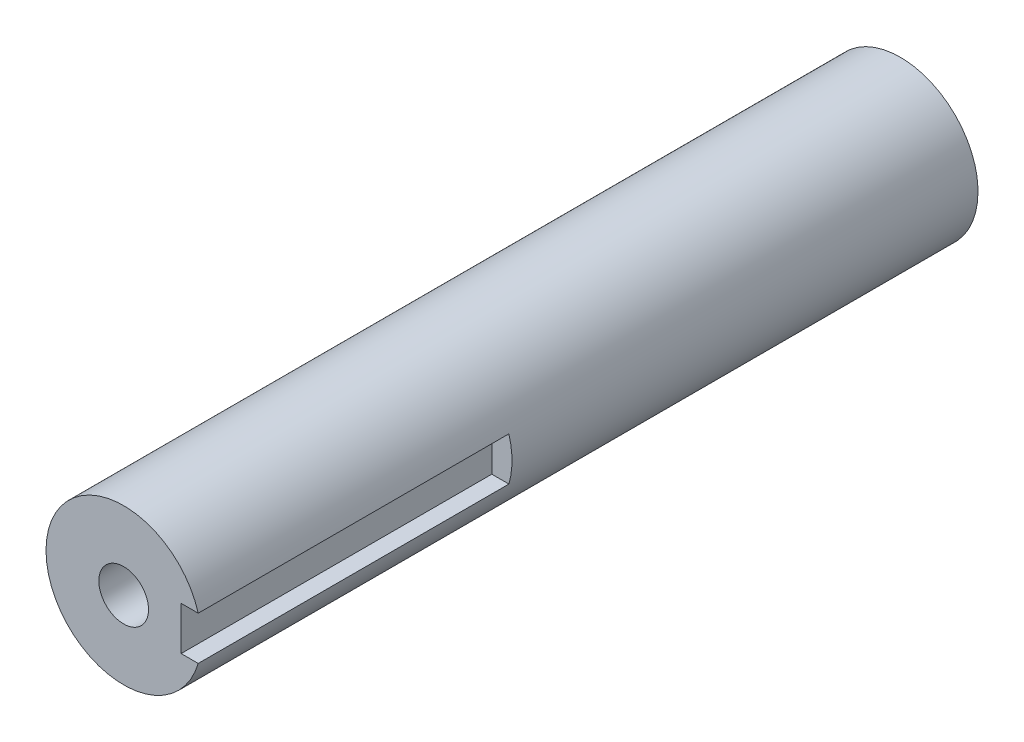
SolidWorks part; units mm, degrees
ref_plane "前视基准面" through (0, 0, 0) normal (0, 0, 1) x (1, 0, 0)
ref_plane "上视基准面" through (0, 0, 0) normal (0, 1, 0) x (1, 0, 0)
ref_plane "右视基准面" through (0, 0, 0) normal (1, 0, 0) x (0, 0, -1)
sketch "草图1" plane through (0, 0, 0) normal (0, 0, 1) x (0, -1, 0)
  circle A0 centre (0, 0) radius 25
  dimension "D1" = 50
extrude "凸台-拉伸1" add sketch "草图1" along normal blind 250
sketch "草图2" plane through (0, 0, 250) normal (0, 0, 1) x (0, -1, 0)
  line L0 (-996.6015, -25) -> (49003.3985, -25) construction
  line L1 (0, -1000) -> (0, 49000) construction
  line L3 (-7, 28.5) -> (7, 28.5)
  line L4 (-7, 28.5) -> (-7, 18.5)
  line L5 (-7, 18.5) -> (7, 18.5)
  line L6 (7, 28.5) -> (7, 18.5)
  circle A0 centre (0, 0) radius 25 construction
  dimension "D1" = 14
  dimension "D2" = 53.5
  dimension "D3" = 10
extrude "切除-拉伸1" cut sketch "草图2" against normal blind 100
sketch "草图3" plane through (0, 0, 250) normal (0, 0, 1) x (1, 0, 0)
  circle A0 centre (0, 0) radius 8
  dimension "D1" = 16
extrude "切除-拉伸2" cut sketch "草图3" against normal blind 40
